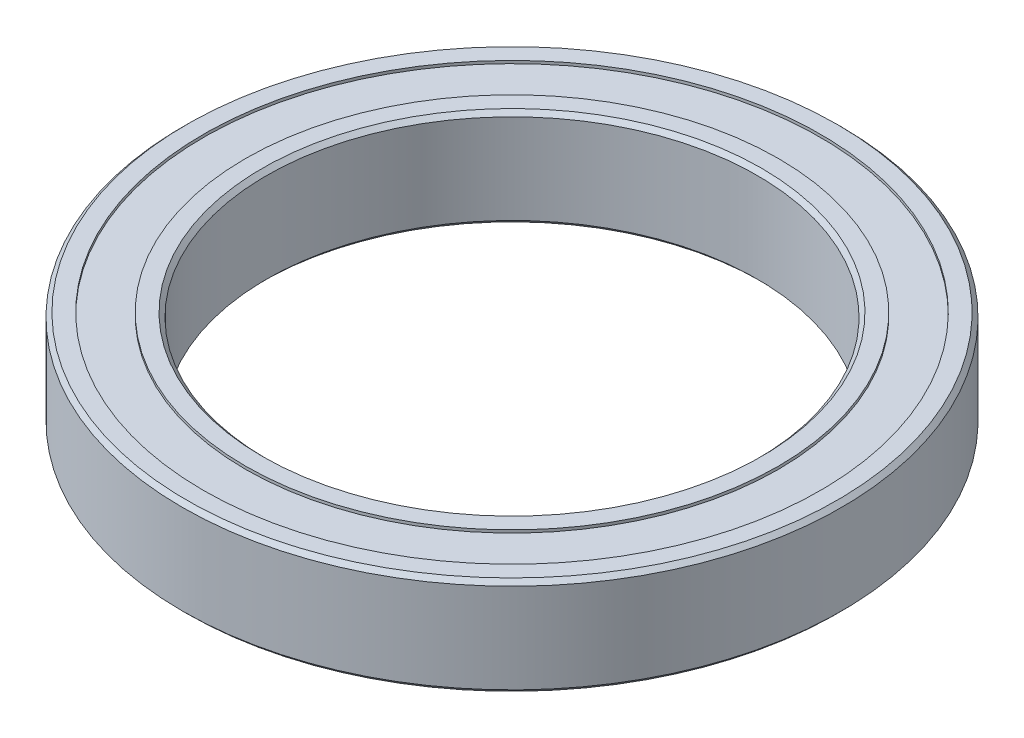
SolidWorks part; units mm, degrees
ref_plane "Front Plane" through (0, 0, 0) normal (0, 0, 1) x (1, 0, 0)
ref_plane "Top Plane" through (0, 0, 0) normal (0, 1, 0) x (1, 0, 0)
ref_plane "Right Plane" through (0, 0, 0) normal (1, 0, 0) x (0, 0, -1)
sketch "Sketch1" plane through (0, 0, 0) normal (0, 1, 0) x (1, 0, 0)
  circle A0 centre (0, 0) radius 17.5
  circle A1 centre (0, 0) radius 23.5
  dimension "D1" = 47
  dimension "D2" = 35
extrude "Boss-Extrude1" add sketch "Sketch1" along normal blind 7
sketch "Sketch2" plane through (0, 7, 0) normal (0, 1, 0) x (1, 0, 0)
  circle A2 centre (0, 0) radius 19
  circle A3 centre (0, 0) radius 19
  circle A5 centre (0, 0) radius 22
  circle A6 centre (0, 0) radius 22
  dimension "D1" = 1.5
  dimension "D2" = 1.5
extrude "Cut-Extrude1" cut sketch "Sketch2" against normal blind 0.2
chamfer "Chamfer1" distance 0.3 angle 45 4 edges at (0, 0, 23.5) (0, 7, 23.5) (0, 0, 17.5) (0, 7, 17.5)
sketch "Sketch3" plane through (0, 0, 0) normal (0, -1, 0) x (1, 0, 0)
  circle A0 centre (0, 0) radius 19 construction
  circle A1 centre (0, 0) radius 22
  circle A2 centre (0, 0) radius 22
  circle A3 centre (0, 0) radius 19
  dimension "D1" = 0
extrude "Cut-Extrude2" cut sketch "Sketch3" against normal blind 0.2
